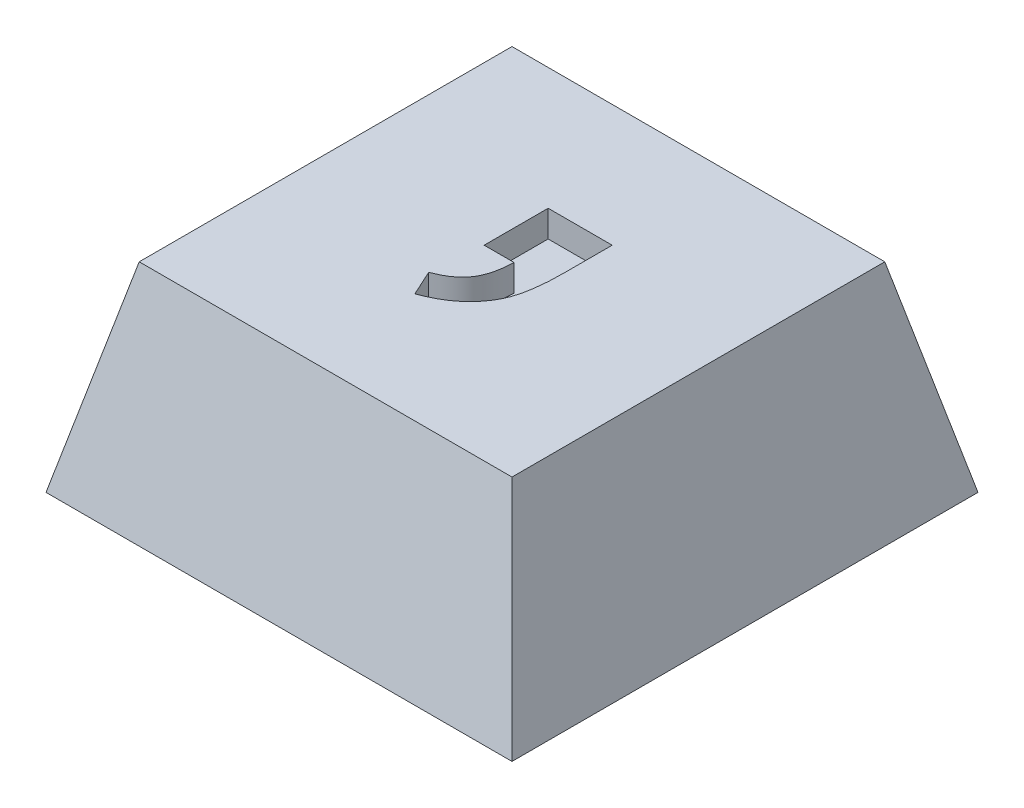
SolidWorks part; units mm, degrees
ref_plane "Front Plane" through (0, 0, 0) normal (0, 0, 1) x (1, 0, 0)
ref_plane "Top Plane" through (0, 0, 0) normal (0, 1, 0) x (1, 0, 0)
ref_plane "Right Plane" through (0, 0, 0) normal (1, 0, 0) x (0, 0, -1)
sketch "Sketch1" plane through (0, 0, 0) normal (0, 1, 0) x (1, 0, 0)
  line L1 (0, 0) -> (7, 0)
  line L2 (0, 0) -> (0, 7)
  line L3 (0, 7) -> (7, 7)
  line L4 (7, 0) -> (7, 7)
  dimension "D1" = 7
  dimension "D2" = 7
extrude "Boss-Extrude1" add sketch "Sketch1" along normal blind 3
sketch "Sketch2" plane through (0, 0, 0) normal (0, 0, 1) x (1, 0, 0)
  line L0 (0, 0) -> (0.7, 3)
  line L1 (0, 3) -> (7, 3) construction
  line L2 (0.7, 3) -> (0, 3)
  line L3 (0, 3) -> (0, 0)
  line L4 (7, 0) -> (6.3, 3)
  line L5 (6.3, 3) -> (7, 3)
  line L6 (7, 3) -> (7, 0)
  dimension "D1" = 0.7
  dimension "D2" = 0.7
extrude "Cut-Extrude1" cut sketch "Sketch2" against normal blind 7
sketch "Sketch3" plane through (0, 0, 0) normal (1, 0, 0) x (0, 0, -1)
  line L0 (0, 0) -> (0.7, 3)
  line L1 (7, 3) -> (0, 3) construction
  line L2 (0.7, 3) -> (0, 3)
  line L3 (0, 3) -> (0, 0)
  line L4 (7, 3) -> (6.3, 3)
  line L5 (6.3, 3) -> (7, 0)
  line L6 (7, 3) -> (7, 0)
  dimension "D1" = 0.7
  dimension "D2" = 0.7
extrude "Cut-Extrude2" cut sketch "Sketch3" along normal blind 11
sketch "Sketch4" plane through (0, 0, 0) normal (0, -1, 0) x (1, 0, 0)
  line L0 (3.5, 0) -> (3.5, -7) construction
  line L1 (0, 0) -> (7, 0) construction
  line L2 (7, -7) -> (0, -7) construction
  line L3 (0, -3.5) -> (7, -3.5) construction
  line L4 (0, -7) -> (0, 0) construction
  line L5 (7, 0) -> (7, -7) construction
  circle A0 centre (3.5, -3.5) radius 1.8
  dimension "D1" = 3.6
extrude "Cut-Extrude3" cut sketch "Sketch4" against normal blind 0.8
sketch "Sketch5" plane through (0, 3, 0) normal (0, 1, 0) x (1, 0, 0)
  text T0 "," font "Arial" height 5
extrude "Cut-Extrude4" cut sketch "Sketch5" against normal blind 0.4
